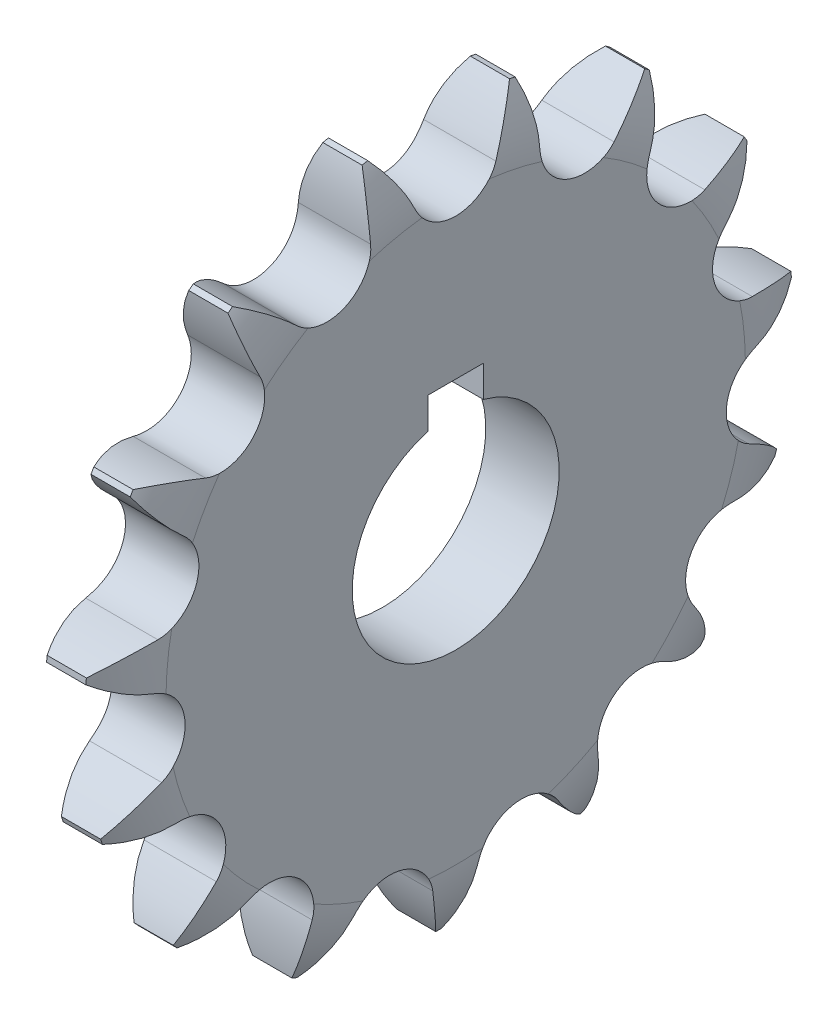
SolidWorks part; units mm, degrees
ref_plane "Plane1" through (0, 0, 0) normal (0, 0, 1) x (1, 0, 0)
ref_plane "Plane2" through (0, 0, 0) normal (0, 1, 0) x (1, 0, 0)
ref_plane "Plane3" through (0, 0, 0) normal (1, 0, 0) x (0, 0, -1)
sketch "Clipboard" plane through (0, 0, 0) normal (0, 1, 0) x (1, 0, 0)
  line L0 (0, 0) -> (9.2004, -2.4653)
  line L1 (-15, 0) -> (100, 0) construction
  line L2 (0, 0) -> (-0.8203, 0.9272)
  line L3 (0, 0) -> (-8.8973, 3.4006)
  line L4 (0, 0) -> (2.9944, 0.8023)
  line L5 (0, 0) -> (-46.8476, -17.4728)
  line L6 (0, 0) -> (-4.4098, -2.9753)
  line L7 (-0.8203, 0.9272) -> (47.2432, 14.7092)
  line L8 (-76.2, 38.1) -> (-74.4, 38.1)
  line L9 (-73.3242, 40.7328) -> (-72.926, 40.7699)
  line L10 (-73.4529, 9.1872) -> (-63.2129, 9.1872)
  circle A0 centre (0, 0) radius 3.175
  circle A1 centre (0, 0) radius 17.7306
  circle A2 centre (0, 0) radius 37.5
  dimension "Dr" = 6.35
  dimension "MHD" = 35.4612
  dimension "Hub_dia" = 75
  dimension "Num_teeth" = 15
  dimension "Pitch" = 9.525
  dimension "Width" = 3.1
  dimension "Side_relief" = 1.238
  dimension "Side_radius" = 9.525
  dimension "Overall_len" = 50
  dimension "Show_teeth" = 15
  dimension "Thickness" = 5.3196
  dimension "OAL" = 50.0005
  dimension "T_dim" = 1.8
  dimension "Fillet_rad" = 0.4
  dimension "Face_width" = 5.32
  dimension "Num_strands" = 1
  dimension "Transv_pitch" = 10.24
  dimension "Plate_wid" = 8.26
sketch "BasProSke" plane through (0, 0, 0) normal (0, 1, 0) x (1, 0, 0)
  line L0 (-10, 0) -> (60, 0) construction
  line L1 (0, 0) -> (0, 20.9886)
  line L2 (0, 0) -> (5.3196, 0)
  line L3 (5.3196, 0) -> (5.3196, 20.9886)
  line L4 (4.0816, 25.6845) -> (1.238, 25.6845)
  arc A0 (0, 20.9886) -> (1.238, 25.6845) centre (9.525, 20.9886) cw
  arc A1 (5.3196, 20.9886) -> (4.0816, 25.6845) centre (-4.2054, 20.9886) ccw
  dimension "Thickness" = 5.3196
  dimension "D1" = 9.525
  dimension "G1" = 1.238
  dimension "G2" = 1.238
  dimension "Diameter" = 51.369
revolve "Base-Revolve" add sketch "BasProSke" angle 360 about L0
sketch "TooCutSke" plane through (0, 0, 0) normal (1, 0, 0) x (0, 0, -1)
  line L0 (0, 22.9381) -> (2.9518, 21.6851) construction
  line L1 (0, 0) -> (0, 107) construction
  line L2 (0, 22.9381) -> (-10, 22.9381) construction
  line L3 (0, 22.9381) -> (-2.9518, 21.6851) construction
  arc A0 (2.9518, 21.6851) -> (5.5304, 25.5938) centre (14.876, 16.6236) cw
  arc A1 (2.9518, 21.6851) -> (-2.9518, 21.6851) centre (0, 22.9381) cw
  arc A2 (-2.9518, 21.6851) -> (-5.5304, 25.5938) centre (-14.876, 16.6236) ccw
  arc A3 (5.5304, 25.5938) -> (-5.5304, 25.5938) centre (0, 0) ccw
  dimension "R1" = 3.2067
  dimension "R2" = 12.954
  dimension "Overcut" = 26.1845
  dimension "Seat_radius" = 22.9381
  dimension "X" = 134
extrude "ToothCut" cut sketch "TooCutSke" along normal through all
pattern_circular "TeethCuts" count 15 every 24 about axis through (-10, 0, 0) along (1, 0, 0) of "ToothCut"
sketch "HubNeaOneSke" plane through (0, 0, 0) normal (-1, 0, 0) x (0, 0, 1)
  circle A0 centre (0, 0) radius 17.7306
  dimension "Diameter" = 35.4612
extrude "HubNearOne" [suppressed] add sketch "HubNeaOneSke" along normal blind 44.6809
fillet "HubNearOneFillet" [suppressed] radius 0.4
sketch "HubNeaBotSke" plane through (0, 0, 0) normal (-1, 0, 0) x (0, 0, 1)
  circle A0 centre (0, 0) radius 17.7306
  dimension "Diameter" = 35.4612
extrude "HubNearBoth" [suppressed] add sketch "HubNeaBotSke" along normal blind 22.3405
fillet "HubNearBothFillet" [suppressed] radius 0.4
ref_plane "FarPln" through (5.3196, 0, 0) normal (1, 0, 0) x (0, 0, -1)
sketch "HubFarSke" plane through (5.3196, 0, 0) normal (1, 0, 0) x (0, 0, -1)
  circle A0 centre (0, 0) radius 17.7306
  dimension "Diameter" = 35.4612
extrude "HubFar" [suppressed] add sketch "HubFarSke" along normal blind 22.3405
fillet "HubFarFillet" [suppressed] radius 0.4
sketch "BorSke" plane through (0, 0, 0) normal (1, 0, 0) x (0, 0, -1)
  circle A0 centre (0, 0) radius 5
  dimension "Diameter" = 10
extrude "Bore" cut sketch "BorSke" along normal mid plane 100.001
sketch "KeySke" plane through (0, 0, 0) normal (1, 0, 0) x (0, 0, -1)
  line L0 (-2, 0) -> (-2, 6.8)
  line L1 (-2, 6.8) -> (2, 6.8)
  line L2 (2, 6.8) -> (2, 0)
  line L3 (0, 0) -> (0, 34) construction
  line L4 (-2, 0) -> (2, 0)
  dimension "Offset" = 6.8
  dimension "Width" = 4
extrude "Keyway" [suppressed] cut sketch "KeySke" along normal mid plane 100.001
pattern_circular "Keyway2" [suppressed] count 2 every 90 about axis through (-10, 0, 0) along (1, 0, 0)
sketch "Sketch1" plane through (5.3196, 0, 0) normal (1, 0, 0) x (0, 0, -1)
  circle A0 centre (0, 0) radius 15
  circle A1 centre (0, 0) radius 7.5
  dimension "D1" = 15
  dimension "D2" = 30
extrude "Boss-Extrude1" add sketch "Sketch1" along normal offset from surface (24.6804 mm away) 30 up to face at (0, 0, -5)
sketch "Sketch3" plane through (5.3196, 0, 0) normal (1, 0, 0) x (0, 0, -1)
  circle A1 centre (0, 0) radius 7.5
  circle A2 centre (0, 0) radius 7.5
  dimension "D1" = 0
extrude "Cut-Extrude2" cut sketch "Sketch3" against normal blind 18.5
sketch "Sketch2" plane through (30, 0, 0) normal (1, 0, 0) x (0, 0, -1)
  circle A0 centre (0, 0) radius 17.7976
extrude "Cut-Extrude1" cut sketch "Sketch2" against normal up to surface (24.6804 mm away) up to face at (5.3196, 0, 15)
sketch "Sketch5" plane through (5.3196, 0, 0) normal (1, 0, 0) x (0, 0, -1)
  line L0 (-2, 9.5) -> (-2, 5.5)
  line L1 (-2, 9.5) -> (2, 9.5)
  line L2 (-2, 5.5) -> (2, 5.5)
  line L3 (2, 9.5) -> (2, 5.5)
  line L4 (-2, 9.5) -> (2, 5.5) construction
  line L5 (-2, 5.5) -> (2, 9.5) construction
  line L6 (0, 7.5) -> (0, 0) construction
  circle A0 centre (0, 0) radius 7.5 construction
  point P1 (0, 7.5)
  dimension "D1" = 4
extrude "Cut-Extrude5" cut sketch "Sketch5" against normal through all
equation "' \"Pitch@Clipboard\" = 12.7"
equation "' \"Num_strands@Clipboard\" = 1"
equation "' \"Num_teeth@Clipboard\" = 9"
equation "' \"Hub_dia@Clipboard\" = 50"
equation "' \"Overall_len@Clipboard\" = 3"
equation "' \"Diameter@BorSke\" = 12"
equation "' \"T_dim@Clipboard\" = 1"
equation "' \"Width@KeySke\" = 2"
equation "' \"Dr@Clipboard\" = 8.51"
equation "' \"Face_width@Clipboard\" = 7.2"
equation "' \"Side_radius@Clipboard\" = 12.7"
equation "' \"Side_relief@Clipboard\" = 1.27"
equation "' \"Transv_pitch@Clipboard\" = 13.92"
equation "' \"Show_teeth@Clipboard\" = 9"
equation "' \"Fillet_rad@Clipboard\" = 0.6"
equation "' \"Plate_wid@Clipboard\" = 11.8"
equation "\"Num_teeth@Clipboard\" = int( \"Num_teeth@Clipboard\" )"
equation "\"Num_teeth@Clipboard\" = ((sgn( \"Num_teeth@Clipboard\" - 5.0)+1)*( \"Num_teeth@Clipboard\" - 5.0))/2 +5.0"
equation "\"Num_teeth@Clipboard\" = ((sgn( \"Num_teeth@Clipboard\" - 200.0)-1)*( \"Num_teeth@Clipboard\" - 200.0))/-2 +200.0"
equation "\"MHD@Clipboard\" = \"Pitch@Clipboard\" * (1.0 / tan(3.14159265 / \"Num_teeth@Clipboard\" )) - 1.04 * \"Plate_wid@Clipboard\" - 0.76"
equation "\"Thickness@Clipboard\"  = \"Face_width@Clipboard\" + (\"Num_strands@Clipboard\" - 1) * \"Transv_pitch@Clipboard\""
equation "\"OAL@Clipboard\" = \"Thickness@Clipboard\" + 2 * \"Fillet_rad@Clipboard\" + 1"
equation "\"MHD@Clipboard\" = ((sgn( \"MHD@Clipboard\" - \"Hub_dia@Clipboard\" )-1)*( \"MHD@Clipboard\" - \"Hub_dia@Clipboard\" ))/-2+ \"Hub_dia@Clipboard\""
equation "\"OAL@Clipboard\" = ((sgn( \"OAL@Clipboard\" - \"Overall_len@Clipboard\" )+1)*( \"OAL@Clipboard\" - \"Overall_len@Clipboard\" ))/2 + \"Overall_len@Clipboard\" + 0.0005"
equation "\"Num_teeth@TeethCuts\" = int( \"Show_teeth@Clipboard\" ) + 1"
equation "\"Num_teeth@TeethCuts\" = ((sgn( \"Num_teeth@TeethCuts\" - \"Num_teeth@Clipboard\" )-1)*( \"Num_teeth@TeethCuts\" - \"Num_teeth@Clipboard\" ))/-2+ \"Num_teeth@Clipboard\""
equation "\"Num_teeth@TeethCuts\" = ((sgn( \"Num_teeth@TeethCuts\" - 2.0)+1)*( \"Num_teeth@TeethCuts\" - 2.0))/2 +2.0"
equation "\"Angle@TeethCuts\" = 360.0 / \"Num_teeth@Clipboard\""
equation "\"Seat_radius@TooCutSke\" = ( \"Pitch@Clipboard\" / 2.0) / sin(3.14159265 / \"Num_teeth@Clipboard\" ) - \"Dr@Clipboard\" / 2.0 + \"Dr@Clipboard\" * 0.505"
equation "\"R1@TooCutSke\"  = \"Dr@Clipboard\" * 0.505"
equation "\"X@TooCutSke\" = 140.0 - (90.0 / \"Num_teeth@Clipboard\")"
equation "\"R2@TooCutSke\" = 0.12 * \"Dr@Clipboard\" * ( \"Num_teeth@Clipboard\" + 2.0)"
equation "\"Overcut@TooCutSke\" = 0.5 + 0.625 * \"Pitch@Clipboard\" - 0.5 * \"Dr@Clipboard\"  +  \"Pitch@Clipboard\" / 2.0 / sin(3.14159265 / \"Num_teeth@Clipboard\" )"
equation "\"Diameter@BasProSke\" = 2.0 * ( 0.625 * \"Pitch@Clipboard\" - 0.5 * \"Dr@Clipboard\"  +  \"Pitch@Clipboard\" / 2.0 / sin(3.14159265 / \"Num_teeth@Clipboard\" ))"
equation "\"Thickness@BasProSke\"  = \"Thickness@Clipboard\""
equation "\"G1@BasProSke\" =  \"Side_relief@Clipboard\""
equation "\"G2@BasProSke\" =  \"Side_relief@Clipboard\""
equation "\"D1@BasProSke\" =  \"Side_radius@Clipboard\""
equation "\"Diameter@HubNeaOneSke\" = \"MHD@Clipboard\""
equation "\"Length@HubNearOne\" = \"OAL@Clipboard\" - \"Thickness@BasProSke\""
equation "\"Diameter@HubNeaBotSke\" = \"MHD@Clipboard\""
equation "\"Length@HubNearBoth\" = ( \"OAL@Clipboard\" - \"Thickness@BasProSke\" ) / 2.0"
equation "\"D1@HubNearOneFillet\" = \"Fillet_rad@Clipboard\""
equation "\"D1@HubNearBothFillet\" = \"Fillet_rad@Clipboard\""
equation "\"Thickness@FarPln\" = \"Thickness@BasProSke\""
equation "\"Diameter@HubFarSke\" = \"MHD@Clipboard\""
equation "\"Length@HubFar\" = ( \"OAL@Clipboard\" - \"Thickness@BasProSke\" ) / 2.0"
equation "\"D1@HubFarFillet\" = \"Fillet_rad@Clipboard\""
equation "\"D1@Bore\" = \"OAL@Clipboard\" * 2.0"
equation "\"D1@Keyway\" = \"OAL@Clipboard\" * 2.0"
equation "\"Offset@KeySke\" = \"T_dim@Clipboard\" + \"Diameter@BorSke\" / 2.0"
